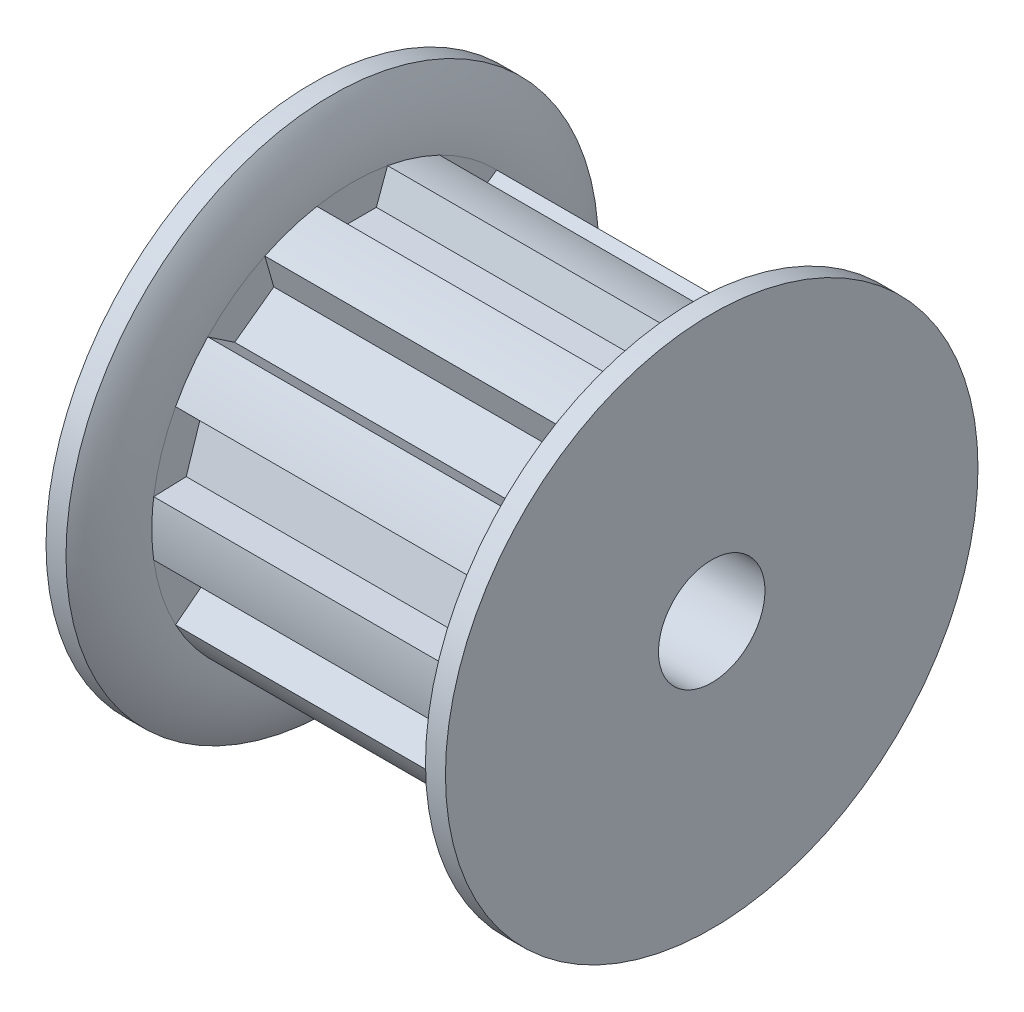
SolidWorks part; units mm, degrees
ref_plane "Front Plane" through (0, 0, 0) normal (0, 0, 1) x (1, 0, 0)
ref_plane "Top Plane" through (0, 0, 0) normal (0, 1, 0) x (1, 0, 0)
ref_plane "Right Plane" through (0, 0, 0) normal (1, 0, 0) x (0, 0, -1)
sketch "Sketch2" plane through (0, 0, 0) normal (1, 0, 0) x (0, 0, -1)
  line L3 (0, 0) -> (0, 6.325) construction
  line L6 (0, 6.325) -> (0, 7.525) construction
  line L7 (-1.325, 7.4074) -> (-0.9072, 6.2596)
  line L8 (1.325, 7.4074) -> (0.9072, 6.2596)
  line L9 (0, -2.2) -> (0, -3.2) construction
  line L10 (0, 8.025) -> (0, 7.525) construction
  line L12 (-0.9072, 6.2596) -> (0.9072, 6.2596)
  line L15 (0, 0) -> (0, -2.2) construction
  circle A0 centre (0, 0) radius 8.025 construction
  circle A1 centre (0, 0) radius 6.325 construction
  arc A7 (1.325, 7.4074) -> (-1.325, 7.4074) centre (0, 0) ccw
  dimension "D1" = 40
  dimension "D3" = 0.5
  dimension "D2" = 1.2
  dimension "D4" = 2.65
sketch "Sketch1" plane through (0, 0, 0) normal (0, 0, 1) x (1, 0, 0)
  line L0 (-10.5, 0) -> (10.5, 0) construction
  line L1 (-10.5, 2) -> (10.5, 2)
  line L2 (-10.5, 2) -> (-10.5, 4)
  line L3 (-4.5, 10) -> (-3.75, 10)
  line L4 (-3, 7.525) -> (-4.5, 7.525) construction
  line L5 (9.75, 7.525) -> (9.75, 10) construction
  line L6 (-3, 7.525) -> (9, 7.525)
  line L8 (9, 7.525) -> (10.5, 7.525) construction
  line L9 (9.75, 10) -> (10.5, 10)
  line L10 (10.5, 10) -> (10.5, 2)
  line L12 (-7.5, 4) -> (-7.5, 2) construction
  line L13 (-4.5, 10) -> (-4.5, 4)
  line L14 (-4.5, 4) -> (-10.5, 4)
  arc A0 (9, 7.525) -> (9.75, 10) centre (13.4588, 7.525) cw
  arc A1 (-3, 7.525) -> (-3.75, 10) centre (-7.4588, 7.525) ccw
  dimension "Bore Size" = 4
  dimension "Overall Width" = 21
  dimension "Inside Width" = 12
  dimension "Outside Width" = 15
  dimension "Hub Dia" = 8
  dimension "OD" = 20
revolve "Revolve1" add sketch "Sketch1" angle 360 mid plane about L0
sketch "Sketch3" plane through (0, 0, 0) normal (1, 0, 0) x (0, 0, -1)
  line L2 (-1.325, 7.4074) -> (-0.9072, 6.2596) construction
  line L3 (-0.9072, 6.2596) -> (0.9072, 6.2596) construction
  line L4 (1.325, 7.4074) -> (0.9072, 6.2596) construction
  line L5 (-1.325, 7.4074) -> (-0.9072, 6.2596)
  line L6 (-0.9072, 6.2596) -> (0.9072, 6.2596)
  line L7 (1.325, 7.4074) -> (0.9072, 6.2596)
  arc A1 (1.325, 7.4074) -> (-1.325, 7.4074) centre (0, 0) ccw construction
  arc A2 (1.325, 7.4074) -> (-1.325, 7.4074) centre (0, 0) ccw
extrude "Cut-Extrude1" cut sketch "Sketch3" along normal up to vertex (12 mm away) from vertex at -3 up to point (9, 7.525, 0) starting at point (-3, 7.525, 0)
pattern_circular "CirPattern1" count 10 over 360 about axis through (0, 0, 0) along (1, 0, 0) of "Cut-Extrude1"
sketch "Sketch5" plane through (0, 0, 0) normal (0, 0, 1) x (1, 0, 0)
  line L0 (9, 6.7716) -> (9, 5.2139) construction
  point P0 (9, 0)
sketch "Sketch6" plane through (-10.5, 0, 0) normal (-1, 0, 0) x (0, 0, 1)
  circle A0 centre (0, 0) radius 4
  circle A1 centre (0, 0) radius 4 construction
extrude "Cut-Extrude2" cut sketch "Sketch6" against normal up to surface (6 mm away) up to face at (-4.5, 0, 4)
equation "\"D3@Sketch2\" = \"ht@Sketch2\"/2"
equation "\"D2@Sketch2\" = \"hs@Sketch2\"-\"ht@Sketch2\""
